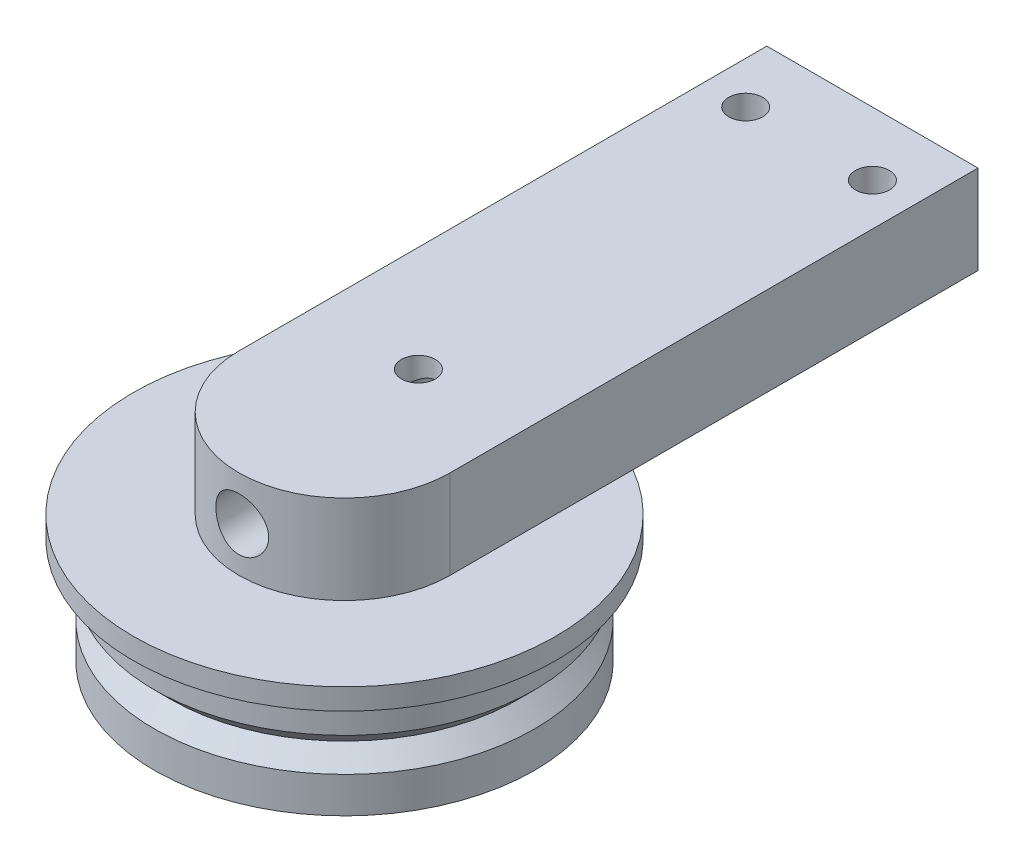
SolidWorks part; units mm, degrees
material "6061 Alloy"
ref_plane "Front Plane" through (0, 0, 0) normal (0, 0, 1) x (1, 0, 0)
ref_plane "Top Plane" through (0, 0, 0) normal (0, 1, 0) x (1, 0, 0)
ref_plane "Right Plane" through (0, 0, 0) normal (1, 0, 0) x (0, 0, -1)
sketch "Sketch1" plane through (0, 0, 0) normal (0, 1, 0) x (1, 0, 0)
  line L0 (-15.875, 0) -> (-15.875, 79.375)
  line L1 (-15.875, 79.375) -> (15.875, 79.375)
  line L2 (15.875, 79.375) -> (15.875, 0)
  arc A0 (-15.875, 0) -> (15.875, 0) centre (0, 0) ccw
  point P14 (0, -15.875)
  dimension "D1" = 95.25
  dimension "D3" = 31.75
extrude "Boss-Extrude1" add sketch "Sketch1" along normal blind 13.3524
sketch "Sketch4" plane through (0, 0, 0) normal (0, -1, 0) x (1, 0, 0)
  circle A0 centre (0, 0) radius 28.575
  dimension "D1" = 57.15
extrude "Boss-Extrude2" add sketch "Sketch4" along normal up to surface (19.05 mm away)
ref_axis "Axis1" through (0, -19.05, 0) along (0, 1, 0)
sketch "Sketch22" plane through (0, 0, 0) normal (0, 0, 1) x (1, 0, 0)
  line L0 (28.575, -8.5725) -> (26.035, -11.1125)
  line L1 (26.035, -11.1125) -> (28.575, -13.6525)
  line L2 (28.575, -8.5725) -> (28.575, -13.6525) construction
  line L3 (28.575, -19.05) -> (28.575, 0) construction
  line L5 (28.575, -8.5725) -> (28.575, -13.6525)
  line L7 (26.035, -11.1125) -> (28.575, -11.1125) construction
  line L8 (28.575, 0) -> (-28.575, 0) construction
  dimension "D1" = 90
  dimension "D2" = 11.1125
  dimension "D3" = 5.08
sketch "Sketch2" plane through (0, 13.3524, 0) normal (0, 1, 0) x (1, 0, 0)
  circle A0 centre (0, 0) radius 6.35
sketch "Sketch5" plane through (0, 0, 0) normal (0, -1, 0) x (1, 0, 0)
  circle A0 centre (0, 0) radius 31.75
  circle A1 centre (0, 0) radius 28.575
  dimension "D1" = 57.15
  dimension "D2" = 63.5
extrude "Boss-Extrude3" add sketch "Sketch5" along normal blind 3.175
hole_wizard "3/8-16 Tapped Hole1" positions "Sketch13" profile "Sketch15" tap size "3/8-16" standard "ANSI Inch" end condition through all
sketch "Sketch13" plane through (0, 0, -79.375) normal (0, 0, -1) x (-1, 0, 0)
  line L0 (-15.875, 6.6762) -> (15.875, 6.6762) construction
  line L1 (-15.875, 13.3524) -> (-15.875, 0) construction
  line L2 (15.875, 13.3524) -> (15.875, 0) construction
  line L4 (0, 0) -> (0, 13.3524) construction
  line L5 (-15.875, 13.3524) -> (15.875, 13.3524) construction
  point P0 (0, 6.6762)
sketch "Sketch15" plane through (0, 6.6762, -79.375) normal (1, 0, 0) x (0, 1, 0)
  line L0 (0, 0) -> (0, 111.125)
  line L1 (0, 111.125) -> (3.9687, 111.125)
  line L2 (3.9687, 111.125) -> (3.9687, 0)
  line L5 (3.9687, 0) -> (0, 0)
  line L11 (0, -6.35) -> (0, 107.95) construction
  dimension "Thru Tap Drill Dia." = 7.9375
  dimension "Thru Tap Drill Depth" = 111.125
cosmetic thread "Hole Thread7" parameters "D2"=9.525
hole_wizard "1/4-20 Tapped Hole2" positions "Sketch20" profile "Sketch21" tap size "1/4-20" standard "ANSI Inch"
sketch "Sketch20" plane through (0, 13.3524, 0) normal (0, 1, 0) x (1, 0, 0)
  line L0 (0, 79.375) -> (0, 0) construction
  line L1 (15.875, 79.375) -> (-15.875, 79.375) construction
  point P0 (-9.525, 69.85)
  point P2 (9.525, 69.85)
  point P5 (0, 11.1125)
  dimension "D2" = 68.2625
sketch "Sketch21" plane through (-9.525, 13.3524, -69.85) normal (1, 0, 0) x (0, 0, 1)
  line L0 (0, 0) -> (0, 119.8038)
  line L1 (0, 119.8038) -> (2.5527, 118.27)
  line L2 (2.5527, 118.27) -> (2.5527, 0)
  line L5 (2.5527, 0) -> (0, 0)
  line L10 (0, 119.8038) -> (-2.5527, 118.27) construction
  line L11 (0, -6.35) -> (0, 107.95) construction
  dimension "Tap Drill Dia." = 5.1054
  dimension "Tap Drill Depth" = 118.27
  dimension "Drill Angle" = 118
cosmetic thread "Hole Thread8" parameters "D1"=95.25, "D2"=6.35
cosmetic thread "Hole Thread9" parameters "D1"=95.25, "D2"=6.35
cosmetic thread "Hole Thread10" parameters "D1"=95.25, "D2"=6.35
revolve "Cut-Revolve2" cut sketch "Sketch22" angle 360 about axis through (0, -19.05, 0) along (0, 1, 0)
extrude "Boss-Extrude6" add sketch "Sketch2" against normal offset from surface (37.9904 mm away) 5.588 up to face at (2.5527, -19.05, -11.1125) offset beyond the face yes
ref_axis "Axis2" through (0, -24.638, 0) along (0, 1, 0)
sketch "Sketch23" plane through (0, 0, 0) normal (1, 0, 0) x (0, 0, -1)
  line L1 (-6.35, -15.8893) -> (-5.9436, -15.8893)
  line L2 (-6.35, -15.8893) -> (-6.35, -16.8799)
  line L3 (-6.35, -16.8799) -> (-5.9436, -16.8799)
  line L4 (-5.9436, -15.8893) -> (-5.9436, -16.8799)
  line L5 (-41.9752, -15.8893) -> (-40.1854, -15.8893) construction
  line L6 (-6.35, -19.05) -> (-6.35, -24.638) construction
  dimension "D1" = 0.9906
  dimension "D2" = 0.4064
revolve "Cut-Revolve4" cut sketch "Sketch23" angle 360 about axis through (0, -24.638, 0) along (0, 1, 0)
